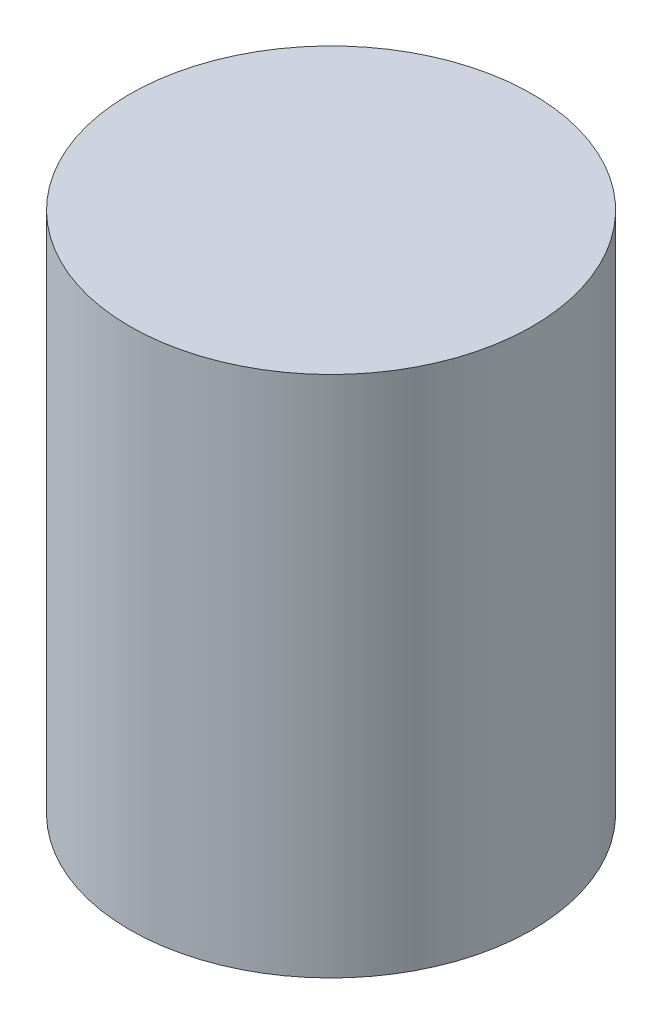
SolidWorks part; units mm, degrees
ref_plane "Front Plane" through (0, 0, 0) normal (0, 0, 1) x (1, 0, 0)
ref_plane "Top Plane" through (0, 0, 0) normal (0, 1, 0) x (1, 0, 0)
ref_plane "Right Plane" through (0, 0, 0) normal (1, 0, 0) x (0, 0, -1)
sketch "Sketch1" plane through (0, 0, 0) normal (0, 1, 0) x (1, 0, 0)
  circle A0 centre (0, 0) radius 19.25
extrude "Boss-Extrude1" add sketch "Sketch1" along normal blind 50
